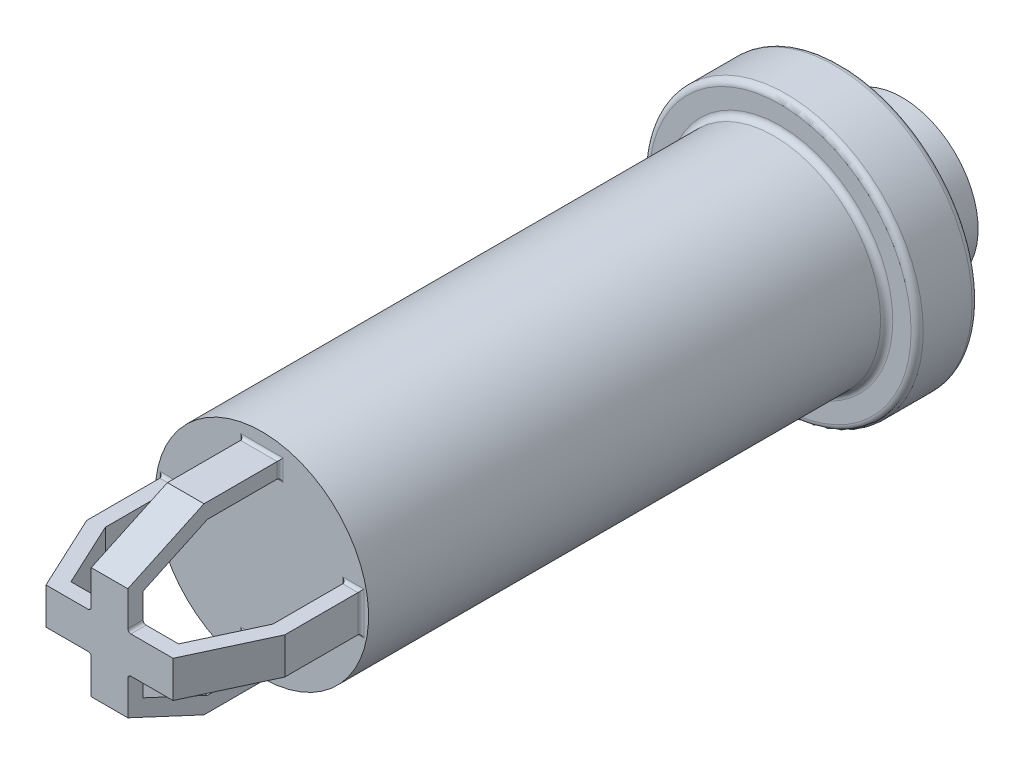
SolidWorks part; units mm, degrees
material "Structural Steel"
ref_plane "Front Plane" through (0, 0, 0) normal (0, 0, 1) x (1, 0, 0)
ref_plane "Top Plane" through (0, 0, 0) normal (0, 1, 0) x (1, 0, 0)
ref_plane "Right Plane" through (0, 0, 0) normal (1, 0, 0) x (0, 0, -1)
sketch "Sketch1" plane through (0, 0, 0) normal (0, 1, 0) x (1, 0, 0)
  line L0 (0, 296.7613) -> (0, 0) construction
  line L1 (0, 260) -> (-25, 260)
  line L2 (-25, 260) -> (-25, 240)
  line L3 (-25, 240) -> (-45, 240)
  line L4 (-45, 240) -> (-45, 220)
  line L5 (-45, 220) -> (-35, 220)
  line L6 (-35, 220) -> (-35, 50)
  line L7 (-35, 50) -> (0, 50)
  line L8 (0, 50) -> (0, 260)
  dimension "D1" = 20
  dimension "D2" = 20
  dimension "D3" = 170
  dimension "D4" = 45
  dimension "D5" = 20
  dimension "D6" = 10
  dimension "D7" = 220
revolve "Revolve1" add sketch "Sketch1" angle 360 about L0
sketch "Sketch5" plane through (0, 0, 0) normal (0, 1, 0) x (1, 0, 0)
  line L0 (0, 81.8591) -> (0, -37.7393) construction
  line L1 (-32.5, 50) -> (-32.5, 25)
  line L2 (-35, 50) -> (35, 50) construction
  line L3 (-32.5, 25) -> (-20.8423, 0)
  line L4 (-20.8423, 0) -> (20.8423, 0)
  line L5 (20.8423, 0) -> (32.5, 25)
  line L6 (32.5, 25) -> (32.5, 50)
  line L7 (-35, 74.9224) -> (-35, -30.085) construction
  line L8 (-35, 220) -> (-35, 50) construction
  line L9 (35, 78.2712) -> (35, -17.8859) construction
  line L10 (-27.5, 50) -> (-27.5, 26.1085)
  line L11 (-27.5, 26.1085) -> (-17.657, 5)
  line L12 (-17.657, 5) -> (17.657, 5)
  line L13 (17.657, 5) -> (27.5, 26.1085)
  line L14 (27.5, 26.1085) -> (27.5, 50)
  line L15 (-32.5, 50) -> (-27.5, 50)
  line L16 (27.5, 50) -> (32.5, 50)
  dimension "D1" = 35
  dimension "D2" = 5
  dimension "D3" = 5
  dimension "D4" = 25
  dimension "D5" = 25
  dimension "D6" = 25
  dimension "D7" = 5
extrude "Boss-Extrude1" add sketch "Sketch5" along normal mid plane 12
sketch "Sketch7" plane through (0, 0, 0) normal (1, 0, 0) x (0, 0, -1)
  line L0 (50, 30) -> (25, 30)
  line L1 (50, 35) -> (50, -35) construction
  line L2 (25, 30) -> (0, 18.3423)
  line L3 (0, 18.3423) -> (0, -18.3423)
  line L4 (0, -18.3423) -> (25, -30)
  line L5 (25, -30) -> (50, -30)
  line L6 (60.0785, -35) -> (-13.7014, -35) construction
  line L7 (58.2623, 35) -> (-9.8421, 35) construction
  line L8 (50, 25) -> (26.1085, 25)
  line L9 (26.1085, 25) -> (5, 15.157)
  line L10 (5, 15.157) -> (5, -15.157)
  line L11 (5, -15.157) -> (26.1085, -25)
  line L12 (26.1085, -25) -> (50, -25)
  line L13 (50, 30) -> (50, 25)
  line L14 (50, -25) -> (50, -30)
  dimension "D1" = 35
  dimension "D2" = 35
  dimension "D3" = 25
  dimension "D4" = 25
  dimension "D5" = 25
  dimension "D6" = 5
  dimension "D7" = 5
  dimension "D8" = 5
extrude "Boss-Extrude2" add sketch "Sketch7" along normal mid plane 12
sketch "Sketch8" plane through (0, 0, 0) normal (0, 1, 0) x (1, 0, 0)
  line L0 (0, 287.0495) -> (0, -28.0921) construction
  line L1 (-25, 220) -> (-15, 220)
  line L2 (-35, 220) -> (35, 220) construction
  line L3 (-25, 220) -> (-25, 60)
  line L4 (-25, 60) -> (0, 60)
  line L5 (-35, 50) -> (35, 50) construction
  line L6 (-35, 220) -> (-35, 50) construction
  line L7 (0, 60) -> (0, 260)
  line L8 (-45, 220) -> (45, 220) construction
  line L9 (-15, 220) -> (-15, 260)
  line L10 (25, 260) -> (-25, 260) construction
  line L11 (-15, 260) -> (0, 260)
  line L12 (-25, 260) -> (-25, 240) construction
  dimension "D1" = 10
  dimension "D2" = 10
  dimension "D3" = 10
revolve "Cut-Revolve1" cut sketch "Sketch8" angle 360 about L0
fillet "Fillet2" radius 1 20 edges at (-30, -6, -50) (-32.5, 0, -50) (6, -27.5, -50) (-6, -27.5, -50) (30, 6, -50) (30, -6, -50) (6, 27.5, -50) (-6, 27.5, -50) (-30, 6, -50) (-27.5, 0, -50) (0, -25, -50) (0, -30, -50) (27.5, 0, -50) (32.5, 0, -50) (0, 25, -50) (0, 30, -50) (6, 6, -2.5) (-6, 6, -2.5) (-6, -6, -2.5) (6, -6, -2.5)
fillet "Fillet3" radius 2 2 edges at (-25, 0, -240) (-35, 0, -220)
fillet "Fillet4" radius 2 4 edges at (-25, 0, -220) (-25, 0, -60) (-45, 0, -240) (-45, 0, -220)
ref_plane "mesh_plane1" [suppressed] through (0, 0, -62) normal (0, 0, 1) x (1, 0, 0)
ref_plane "mesh_plane2" [suppressed] through (0, 0, -218) normal (0, 0, 1) x (1, 0, 0)
split "Split1" [suppressed] bodies to split 104
